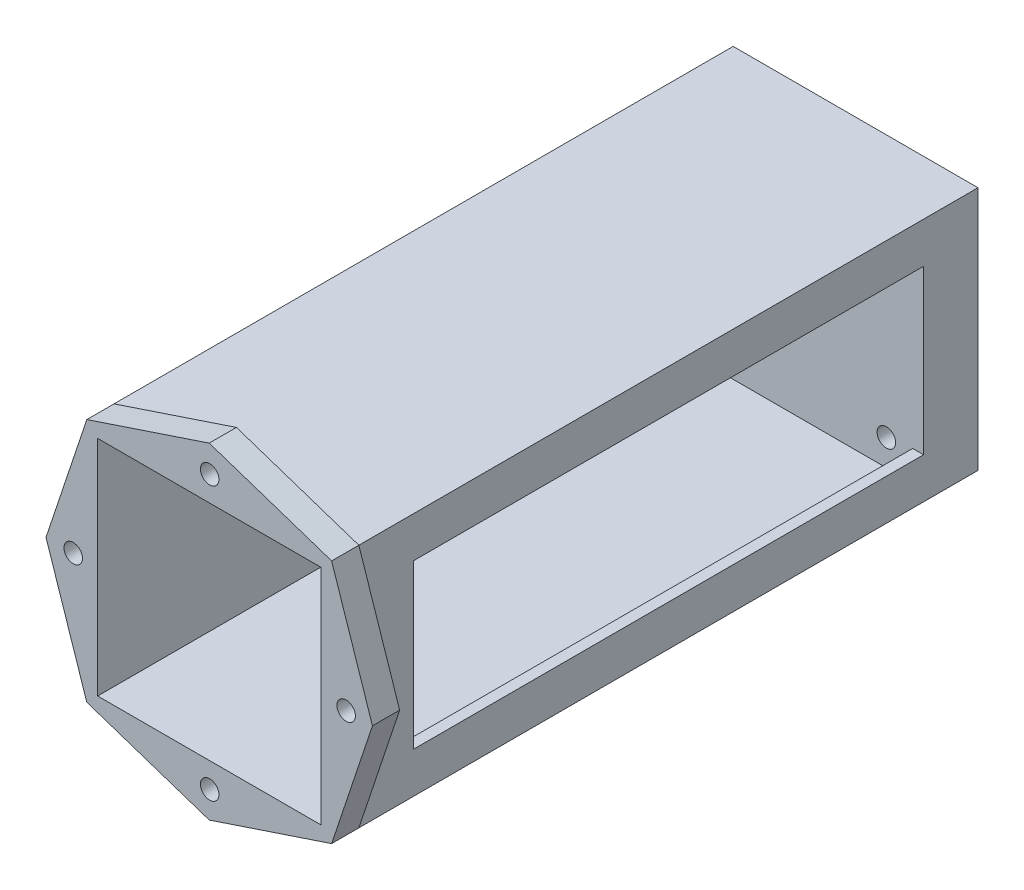
SolidWorks part; units mm, degrees
ref_plane "Piano frontale" through (0, 0, 0) normal (1, 0, 0) x (0, 1, 0)
ref_plane "Piano superiore" through (0, 0, 0) normal (0, 0, 1) x (0, 1, 0)
ref_plane "Piano destro" through (0, 0, 0) normal (0, 1, 0) x (-1, 0, 0)
sketch "Schizzo1" plane through (0, 0, 0) normal (0, 0, 1) x (0, 1, 0)
  line L0 (-22.5, 22.5) -> (-30, 0)
  line L1 (-22.5, -22.5) -> (22.5, -22.5) construction
  line L2 (-22.5, -22.5) -> (-22.5, 22.5) construction
  line L3 (-22.5, 22.5) -> (22.5, 22.5) construction
  line L4 (22.5, -22.5) -> (22.5, 22.5) construction
  line L5 (-22.5, -22.5) -> (22.5, 22.5) construction
  line L6 (-22.5, 22.5) -> (22.5, -22.5) construction
  line L7 (-30, 0) -> (-22.5, -22.5)
  line L8 (-22.5, 22.5) -> (0, 30)
  line L9 (0, 30) -> (22.5, 22.5)
  line L10 (22.5, 22.5) -> (30, 0)
  line L11 (30, 0) -> (22.5, -22.5)
  line L12 (22.5, -22.5) -> (0, -30)
  line L13 (0, -30) -> (-22.5, -22.5)
  line L14 (0, 0) -> (30, 0) construction
  line L15 (0, 0) -> (0, 30) construction
  line L16 (0, 0) -> (-30, 0) construction
  line L17 (0, 0) -> (0, -30) construction
  point P0 (0, 0)
  dimension "D1" = 45
  dimension "D2" = 30
extrude "Estrusione-Estrusione1" add sketch "Schizzo1" against normal blind 5
hole_wizard "Foro per Vite M3-1" positions "Schizzo2" profile "Schizzo3" hole size "M3" standard "ISO" end condition through all
sketch "Schizzo2" plane through (0, 0, 0) normal (0, 0, 1) x (1, 0, 0)
  point P0 (-25, 0)
  dimension "D1" = 25
sketch "Schizzo3" plane through (-25, 0, 0) normal (1, 0, 0) x (0, -1, 0)
  line L0 (0, 0) -> (0, 5)
  line L1 (0, 5) -> (1.7, 5)
  line L2 (1.7, 5) -> (1.7, 0)
  line L5 (1.7, 0) -> (0, 0)
  line L11 (0, -6.35) -> (0, 107.95) construction
  dimension "Thru Hole Dia." = 3.4
  dimension "Thru Hole Depth" = 5
pattern_circular "RipetizioneCircolare1" count 4 over 360 about axis through (0.0844, 0, 0) along (0, 0, 1) of "Foro per Vite M3-1"
sketch "Schizzo4" plane through (0, 0, -5) normal (0, 0, -1) x (1, 0, 0)
  line L1 (-22.5, -22.5) -> (22.5, -22.5)
  line L2 (-22.5, -22.5) -> (-22.5, 22.5)
  line L3 (-22.5, 22.5) -> (22.5, 22.5)
  line L4 (22.5, -22.5) -> (22.5, 22.5)
  line L5 (-22.5, -22.5) -> (22.5, 22.5) construction
  line L6 (-22.5, 22.5) -> (22.5, -22.5) construction
  point P0 (0, 0)
  dimension "D1" = 45
extrude "Estrusione-Estrusione2" add sketch "Schizzo4" along normal blind 103.8
sketch "Schizzo5" plane through (0, 0, -108.8) normal (0, 0, -1) x (1, 0, 0)
  line L8 (20.5, -20.5) -> (20.5, 20.5)
  line L9 (20.5, 20.5) -> (-20.5, 20.5)
  line L10 (-20.5, 20.5) -> (-20.5, -20.5)
  line L11 (-20.5, -20.5) -> (20.5, -20.5)
  line L12 (20.5, -20.5) -> (20.5, 20.5)
  line L13 (20.5, 20.5) -> (-20.5, 20.5)
  line L14 (-20.5, 20.5) -> (-20.5, -20.5)
  line L15 (-20.5, -20.5) -> (20.5, -20.5)
  dimension "D1" = 2
extrude "Taglio-Estrusione1" cut sketch "Schizzo5" against normal through all
sketch "Schizzo6" plane through (22.5, 0, 0) normal (1, 0, 0) x (0, 1, 0)
  line L1 (-15, -108.8) -> (15, -108.8)
  line L2 (-15, -108.8) -> (-15, -15)
  line L3 (-15, -15) -> (15, -15)
  line L4 (15, -108.8) -> (15, -15)
  line L5 (-15, -108.8) -> (15, -15) construction
  line L6 (-15, -15) -> (15, -108.8) construction
  line L8 (22.5, -108.8) -> (-22.5, -108.8) construction
  line L10 (22.5, -5) -> (-22.5, -5) construction
  point P0 (0, -61.9)
  dimension "D1" = 30
  dimension "D2" = 10
extrude "Taglio-Estrusione2" cut sketch "Schizzo6" against normal up to next
sketch "Schizzo7" plane through (0, 0, -108.8) normal (0, 0, -1) x (1, 0, 0)
  line L1 (22.5, 22.5) -> (-22.5, 22.5)
  line L2 (22.5, 22.5) -> (22.5, -22.5)
  line L3 (22.5, -22.5) -> (-22.5, -22.5)
  line L4 (-22.5, 22.5) -> (-22.5, -22.5)
extrude "Estrusione-Estrusione3" add sketch "Schizzo7" along normal blind 10
hole_wizard "Joint-motor-housing" positions "Schizzo10" profile "Schizzo11" hole size "M3" standard "ISO" end condition through all
sketch "Schizzo10" plane through (0, 0, -118.8) normal (0, 0, -1) x (-1, 0, 0)
  line L0 (0, 0) -> (15.52, 0) construction
  line L1 (15.52, 0) -> (15.52, 15.52) construction
  point P7 (15.52, 15.52)
  dimension "D1" = 15.52
sketch "Schizzo11" plane through (-15.52, 15.52, -118.8) normal (1, 0, 0) x (0, 1, 0)
  line L0 (0, 0) -> (0, 118.8)
  line L1 (0, 118.8) -> (1.7, 118.8)
  line L2 (1.7, 118.8) -> (1.7, 0)
  line L5 (1.7, 0) -> (0, 0)
  line L11 (0, -6.35) -> (0, 107.95) construction
  dimension "Thru Hole Dia." = 3.4
  dimension "Thru Hole Depth" = 118.8
pattern_circular "RipetizioneCircolare2" count 4 over 360 about axis through (0.0699, -0.0699, 0) along (0, 0, 1) of "Joint-motor-housing"
hole_wizard "Joint-motor-arm" positions "Schizzo12" profile "Schizzo13" hole size "M5" standard "ISO" end condition through all
sketch "Schizzo12" plane through (0, 0, -118.8) normal (0, 0, -1) x (-1, 0, 0)
  point P0 (0, 0)
sketch "Schizzo13" plane through (0, 0, -118.8) normal (1, 0, 0) x (0, 1, 0)
  line L0 (0, 0) -> (0, 118.8)
  line L1 (0, 118.8) -> (2.75, 118.8)
  line L2 (2.75, 118.8) -> (2.75, 0)
  line L5 (2.75, 0) -> (0, 0)
  line L11 (0, -6.35) -> (0, 107.95) construction
  dimension "Thru Hole Dia." = 5.5
  dimension "Thru Hole Depth" = 118.8
